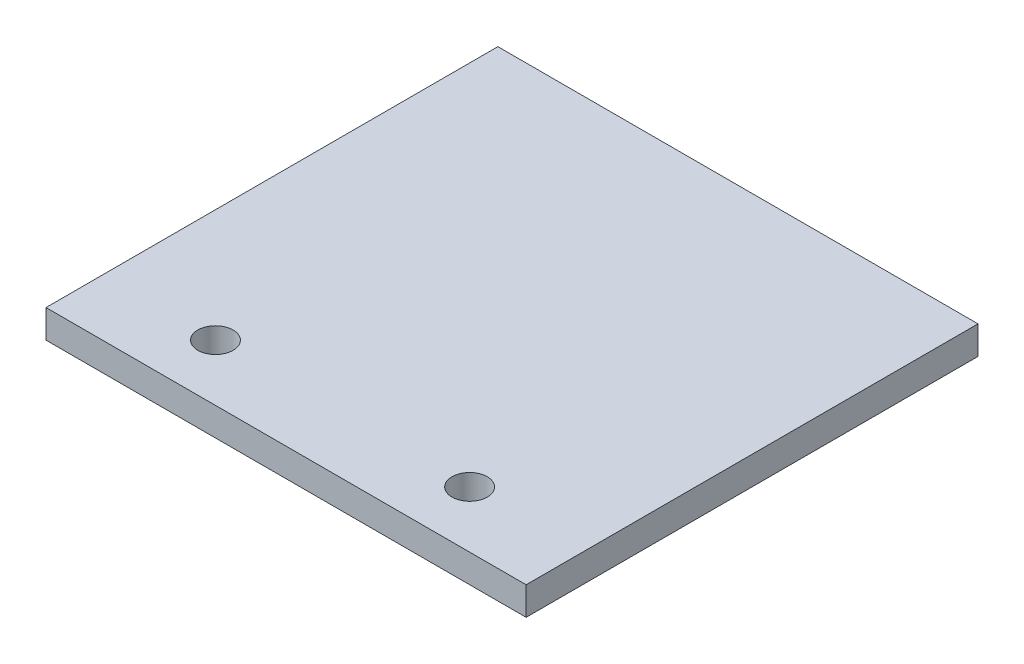
SolidWorks part; units mm, degrees
material "6061 Alloy"
ref_plane "Front Plane" through (0, 0, 0) normal (0, 0, 1) x (1, 0, 0)
ref_plane "Top Plane" through (0, 0, 0) normal (0, 1, 0) x (1, 0, 0)
ref_plane "Right Plane" through (0, 0, 0) normal (1, 0, 0) x (0, 0, -1)
sketch "Sketch1" plane through (0, 0, 0) normal (0, 1, 0) x (1, 0, 0)
  line L1 (-53.975, 50.8) -> (53.975, 50.8)
  line L2 (-53.975, 50.8) -> (-53.975, -50.8)
  line L3 (-53.975, -50.8) -> (53.975, -50.8)
  line L4 (53.975, 50.8) -> (53.975, -50.8)
  line L5 (-53.975, 50.8) -> (53.975, -50.8) construction
  line L6 (-53.975, -50.8) -> (53.975, 50.8) construction
  point P0 (0, 0)
  dimension "D1" = 101.6
  dimension "D2" = 107.95
extrude "Boss-Extrude1" add sketch "Sketch1" along normal blind 6.35
sketch "Sketch2" plane through (0, 6.35, 0) normal (0, 1, 0) x (1, 0, 0)
  line L0 (0, 0) -> (0, -11.2478) construction
  line L1 (0, 0) -> (-15.1024, 0) construction
  line L2 (-53.975, -50.8) -> (53.975, -50.8) construction
  line L3 (-53.975, 50.8) -> (-53.975, -50.8) construction
  circle A0 centre (-28.575, -38.1) radius 3.9688
  circle A1 centre (28.575, -38.1) radius 3.9687
  dimension "D1" = 12.7
  dimension "D2" = 25.4
extrude "Cut-Extrude1" cut sketch "Sketch2" against normal up to next
